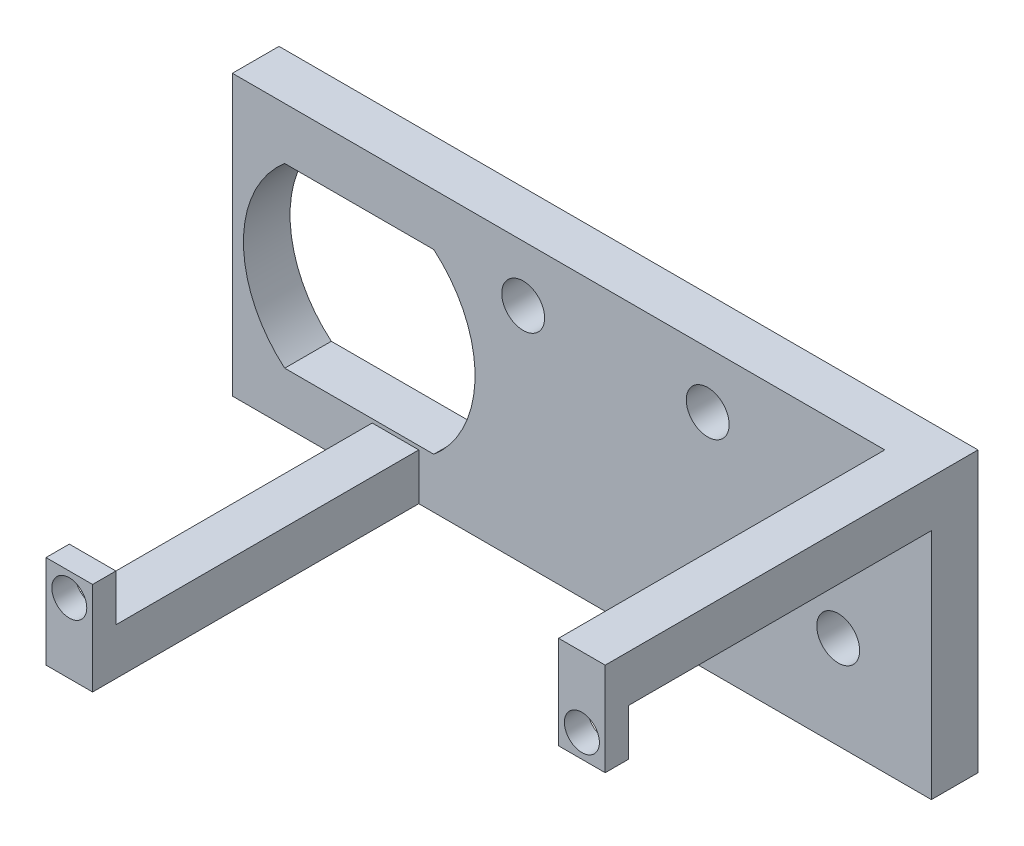
SolidWorks part; units mm, degrees
ref_plane "Front Plane" through (0, 0, 0) normal (0, 0, 1) x (1, 0, 0)
ref_plane "Top Plane" through (0, 0, 0) normal (0, 1, 0) x (1, 0, 0)
ref_plane "Right Plane" through (0, 0, 0) normal (1, 0, 0) x (0, 0, -1)
sketch "Sketch1" plane through (0, 0, 0) normal (0, 0, 1) x (1, 0, 0)
  line L0 (5.9993, 9.0007) -> (20, -5) construction
  line L1 (-30, -15) -> (30, -15)
  line L2 (-30, -15) -> (-30, 15)
  line L3 (-30, 15) -> (30, 15)
  line L4 (30, -15) -> (30, 15)
  line L5 (-30, -15) -> (30, 15) construction
  line L6 (-30, 15) -> (30, -15) construction
  circle A0 centre (-13.8007, 9.0007) radius 2.3
  circle A1 centre (5.9993, 9.0007) radius 2.3
  circle A2 centre (20, -5) radius 2.3
  point P0 (0, 0)
  dimension "D1" = 4.6
  dimension "D7" = 10
  dimension "D3" = 19.8
  dimension "D5" = 19.8
  dimension "D6" = 10
  dimension "D8" = 30
  dimension "D9" = 60
  dimension "D10" = 45
extrude "Boss-Extrude1" add sketch "Sketch1" along normal blind 5
sketch "Sketch3" plane through (0, 0, 5) normal (0, 0, 1) x (1, 0, 0)
  line L1 (30, 15) -> (25, 15)
  line L2 (30, 15) -> (30, 10)
  line L3 (30, 10) -> (25, 10)
  line L4 (25, 15) -> (25, 10)
  line L5 (-30, -15) -> (-25, -15)
  line L6 (-30, -15) -> (-30, -10)
  line L7 (-30, -10) -> (-25, -10)
  line L8 (-25, -15) -> (-25, -10)
  dimension "D1" = 5
extrude "Boss-Extrude2" add sketch "Sketch3" along normal blind 35
sketch "Sketch5" plane through (0, 0, 40) normal (0, 0, 1) x (1, 0, 0)
  line L0 (-25, -15) -> (-25, -10) construction
  line L2 (-30, -10) -> (-25, -10)
  line L3 (-30, -10) -> (-30, -5)
  line L4 (-30, -5) -> (-25, -5)
  line L5 (-25, -10) -> (-25, -5)
  line L6 (30, -15) -> (30, 10) construction
  line L7 (25, 10) -> (30, 10)
  line L8 (25, 10) -> (25, 5)
  line L9 (25, 5) -> (30, 5)
  line L10 (30, 10) -> (30, 5)
  line L11 (25, 15) -> (25, 10) construction
  circle A0 centre (27.5, 7.5) radius 1.875
  circle A1 centre (-27.5, -7.5) radius 1.875
  point P20 (-27.5, -5)
  point P21 (27.5, 5)
  point P22 (-25, -7.5)
  point P23 (25, 7.5)
  dimension "D1" = 3.75
extrude "Boss-Extrude3" add sketch "Sketch5" against normal blind 2.5
sketch "Sketch6" plane through (-30, 0, 0) normal (-1, 0, 0) x (0, 0, 1)
  line L0 (0, 15) -> (5, 15)
  line L1 (5, 15) -> (5, -15)
  line L2 (5, -15) -> (0, -15)
  line L3 (0, -15) -> (0, 15)
extrude "Boss-Extrude4" add sketch "Sketch6" along normal blind 15
sketch "Sketch7" plane through (0, 0, 0) normal (0, 0, -1) x (-1, 0, 0)
  line L0 (13.8007, 9.0007) -> (31.3905, -0.09) construction
  line L1 (23.5228, -9.25) -> (39.2581, -9.25) construction
  line L2 (23.5228, 9.07) -> (39.2581, 9.07) construction
  line L3 (23.5228, -9.25) -> (39.2581, 9.07) construction
  line L4 (23.5228, 9.07) -> (39.2581, -9.25) construction
  line L5 (45, -15) -> (-30, -15) construction
  line L6 (23.3942, 9.42) -> (39.3867, 9.42)
  line L7 (23.3942, -9.6) -> (39.3867, -9.6)
  arc A0 (23.5228, 9.07) -> (23.5228, -9.25) centre (31.3905, -0.09) ccw construction
  arc A1 (39.2581, -9.25) -> (39.2581, 9.07) centre (31.3905, -0.09) ccw construction
  arc A2 (39.3867, -9.6) -> (39.3867, 9.42) centre (31.3905, -0.09) ccw
  arc A3 (23.3942, 9.42) -> (23.3942, -9.6) centre (31.3905, -0.09) ccw
  point P3 (31.3905, -0.09)
  point P8 (31.3905, 0)
  point P9 (13.8007, 9.0007)
  dimension "D3" = 12.075
  dimension "D4" = 5.75
  dimension "D1" = 19.8
  dimension "D2" = 18.32
  dimension "D5" = 0.35
extrude "Cut-Extrude1" cut sketch "Sketch7" against normal up to next
equation "\"shaftHole\"=4.05"
